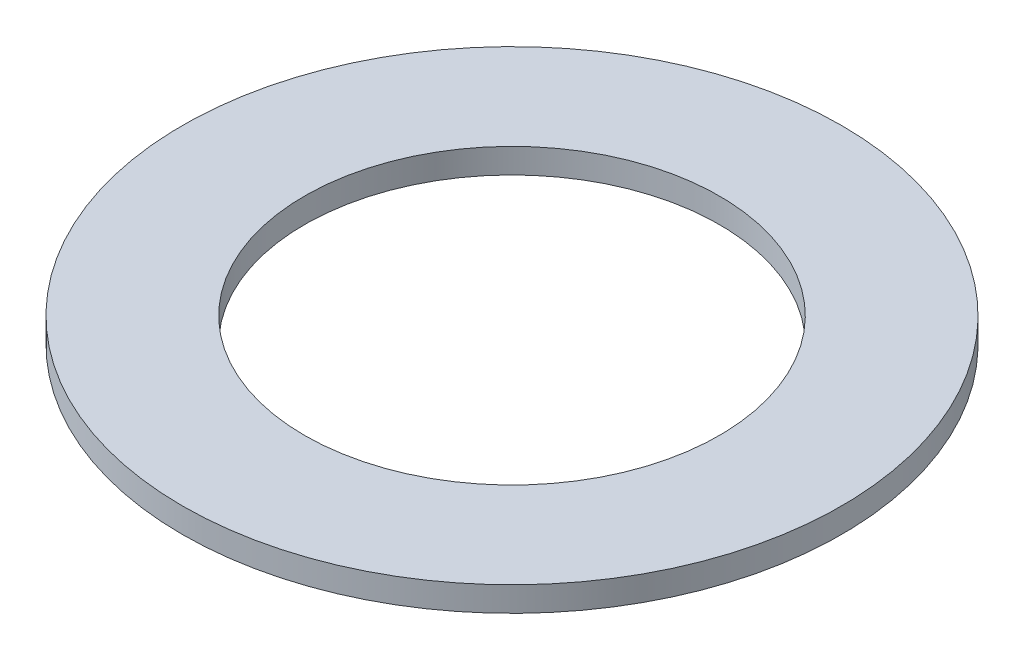
SolidWorks part; units mm, degrees
ref_plane "Front Plane" through (0, 0, 0) normal (0, 0, 1) x (1, 0, 0)
ref_plane "Top Plane" through (0, 0, 0) normal (0, 1, 0) x (1, 0, 0)
ref_plane "Right Plane" through (0, 0, 0) normal (1, 0, 0) x (0, 0, -1)
sketch "Sketch1" plane through (0, 0, 0) normal (0, 1, 0) x (1, 0, 0)
  circle A0 centre (0, 0) radius 5.72
  circle A1 centre (0, 0) radius 3.6
  dimension "D1" = 11.44
  dimension "D2" = 7.2
extrude "Boss-Extrude1" add sketch "Sketch1" along normal blind 0.43
